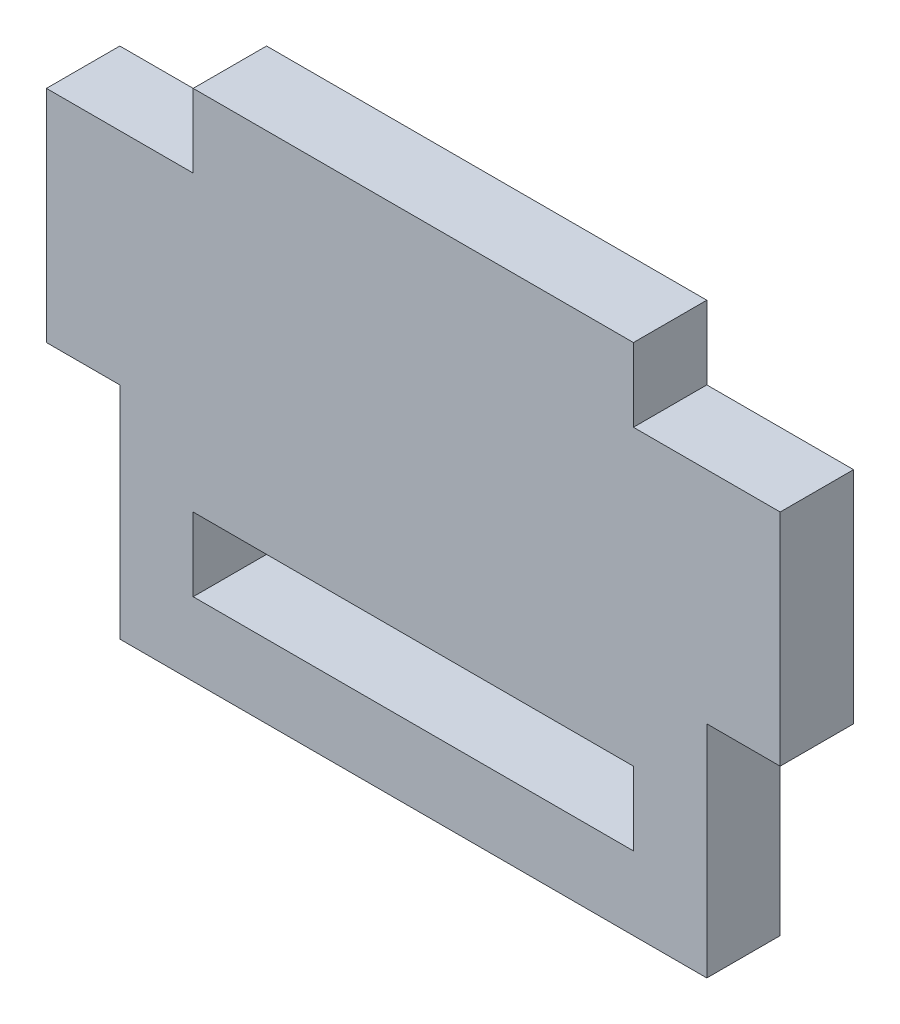
SolidWorks part; units mm, degrees
ref_plane "Front Plane" through (0, 0, 0) normal (0, 0, 1) x (1, 0, 0)
ref_plane "Top Plane" through (0, 0, 0) normal (0, 1, 0) x (1, 0, 0)
ref_plane "Right Plane" through (0, 0, 0) normal (1, 0, 0) x (0, 0, -1)
sketch "Sketch1" plane through (0, 0, 0) normal (0, 0, 1) x (1, 0, 0)
  line L1 (0, 0) -> (50, 0)
  line L2 (0, 0) -> (0, -15)
  line L3 (0, -15) -> (50, -15)
  line L4 (50, 0) -> (50, -15)
  line L5 (5, -15) -> (45, -15)
  line L6 (5, -15) -> (5, -30)
  line L7 (5, -30) -> (45, -30)
  line L8 (45, -15) -> (45, -30)
  line L9 (10, -20) -> (40, -20)
  line L10 (10, -20) -> (10, -25)
  line L11 (10, -25) -> (40, -25)
  line L12 (40, -20) -> (40, -25)
  line L13 (10, 0) -> (40, 0)
  line L14 (10, 0) -> (10, 5)
  line L15 (10, 5) -> (40, 5)
  line L16 (40, 0) -> (40, 5)
  dimension "D1" = 40
  dimension "D2" = 5
  dimension "D3" = 5
  dimension "D4" = 5
  dimension "D5" = 15
  dimension "D6" = 15
  dimension "D7" = 5
  dimension "D8" = 5
  dimension "D9" = 5
  dimension "D10" = 30
  dimension "D11" = 5
extrude "Boss-Extrude1" add sketch "Sketch1" along normal blind 5 contours L1 L16 L15 L14 | L4 L1 L2 L3 | L8 L3 L6 L7 L9 L12 L11 L10
